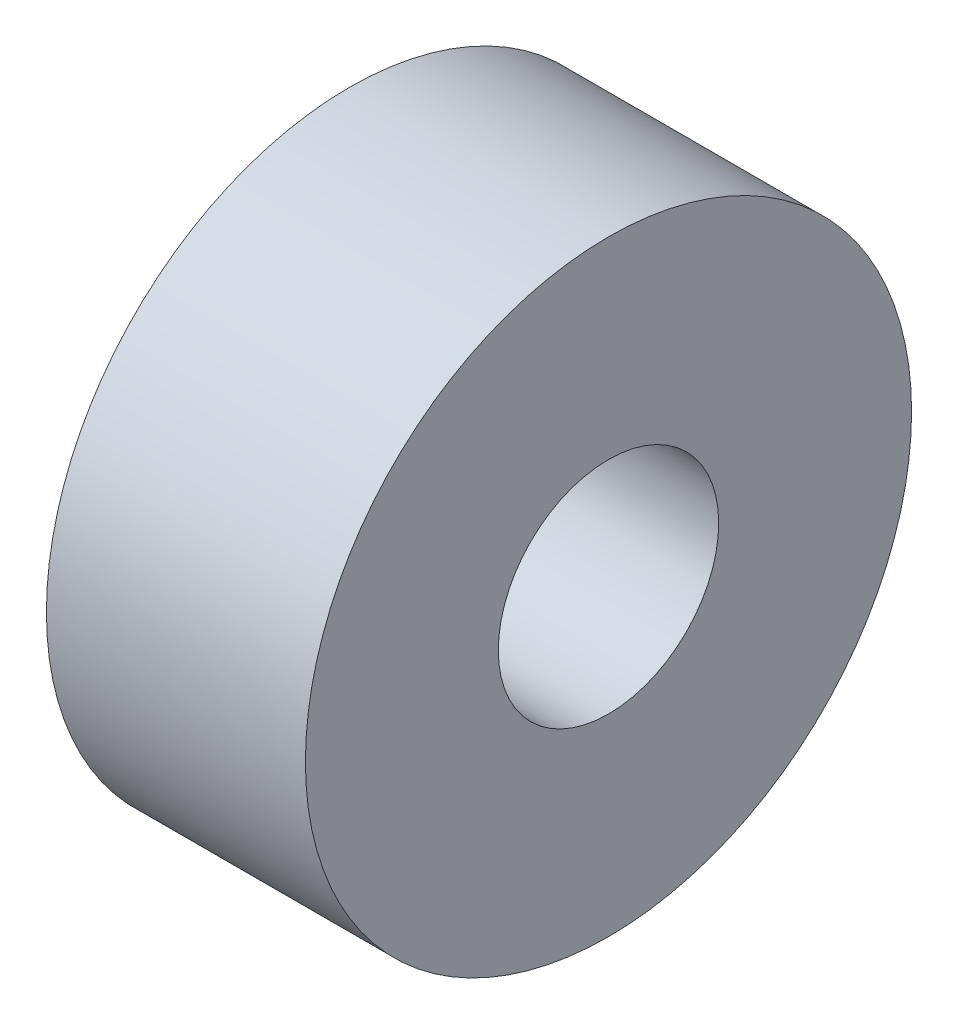
SolidWorks part; units mm, degrees
material "AISI 304"
ref_plane "前视基准面" through (0, 0, 0) normal (0, 0, 1) x (1, 0, 0)
ref_plane "上视基准面" through (0, 0, 0) normal (0, 1, 0) x (1, 0, 0)
ref_plane "右视基准面" through (0, 0, 0) normal (1, 0, 0) x (0, 0, -1)
sketch "草图1" plane through (0, 0, 0) normal (1, 0, 0) x (0, 0, -1)
  circle A0 centre (0, 0) radius 2.75
  dimension "D1" = 5.5
extrude "凸台-拉伸1" add sketch "草图1" along normal blind 2.35
sketch "草图2" plane through (2.35, 0, 0) normal (1, 0, 0) x (0, 0, -1)
  circle A0 centre (0, 0) radius 1
  dimension "D1" = 2
extrude "切除-拉伸1" cut sketch "草图2" against normal through all
